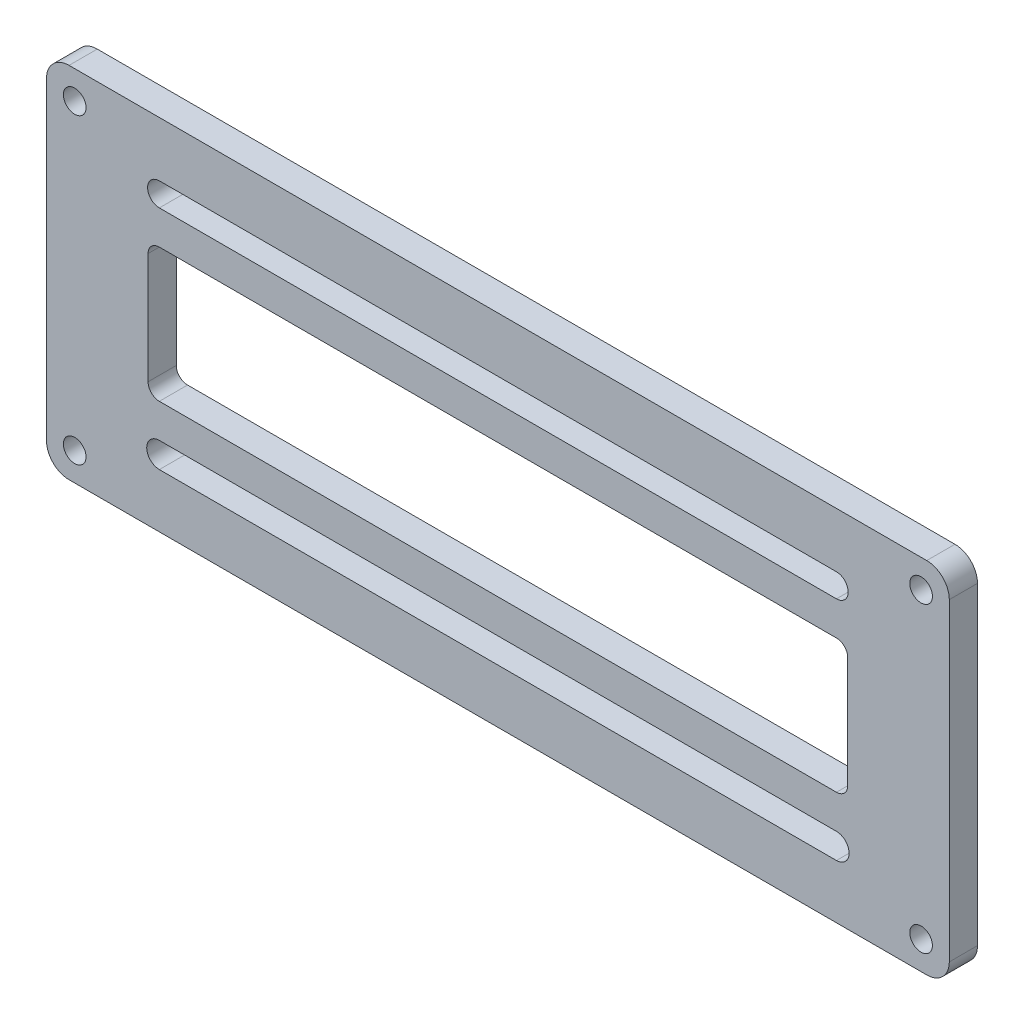
SolidWorks part; units mm, degrees
ref_plane "Front Plane" through (0, 0, 0) normal (0, 0, 1) x (1, 0, 0)
ref_plane "Top Plane" through (0, 0, 0) normal (0, 1, 0) x (1, 0, 0)
ref_plane "Right Plane" through (0, 0, 0) normal (1, 0, 0) x (0, 0, -1)
sketch "Sketch1" plane through (0, 0, 0) normal (0, 0, 1) x (1, 0, 0)
  line L1 (-74.3372, -32.278) -> (128.8628, -32.278)
  line L2 (-74.3372, -32.278) -> (-74.3372, 48.494)
  line L3 (-74.3372, 48.494) -> (128.8628, 48.494)
  line L4 (128.8628, -32.278) -> (128.8628, 48.494)
  dimension "D1" = 80.772
  dimension "D2" = 203.2
extrude "Boss-Extrude1" add sketch "Sketch1" along normal blind 6.35
sketch "Sketch2" plane through (0, 0, 6.35) normal (0, 0, 1) x (1, 0, 0)
  line L0 (128.8628, 48.494) -> (-74.3372, 48.494) construction
  line L1 (128.8628, -32.278) -> (128.8628, 48.494) construction
  line L2 (-74.3372, -32.278) -> (128.8628, -32.278) construction
  line L3 (-74.3372, 48.494) -> (-74.3372, -32.278) construction
  circle A0 centre (-67.9872, 42.144) radius 2.5527
  circle A1 centre (-67.9872, -25.928) radius 2.5527
  circle A2 centre (122.5128, 42.144) radius 2.5527
  circle A3 centre (122.5128, -25.928) radius 2.5527
  dimension "D1" = 5.1054
  dimension "D4" = 5.1054
  dimension "D5" = 6.35
  dimension "D6" = 196.85
  dimension "D7" = 5.1054
  dimension "D8" = 5.1054
  dimension "D9" = 6.35
  dimension "D10" = 6.35
  dimension "D11" = 196.85
  dimension "D12" = 196.85
  dimension "D2" = 6.35
  dimension "D3" = 196.85
extrude "Cut-Extrude1" cut sketch "Sketch2" against normal blind 8.89
sketch "Sketch3" plane through (0, 0, 6.35) normal (0, 0, 1) x (1, 0, 0)
  line L0 (-48.9372, 33.508) -> (103.4628, 33.508) construction
  line L1 (-48.9372, 36.1475) -> (103.4628, 36.1475)
  line L2 (-48.9372, 30.8685) -> (103.4628, 30.8685)
  line L3 (-48.9372, -17.292) -> (103.4628, -17.292) construction
  line L4 (-48.9372, -14.4494) -> (103.4628, -14.4494)
  line L5 (-48.9372, -20.1346) -> (103.4628, -20.1346)
  line L6 (-74.3372, 48.494) -> (-74.3372, -32.278) construction
  line L7 (-74.3372, -32.278) -> (128.8628, -32.278) construction
  line L9 (-48.9372, -6.8294) -> (103.4628, -6.8294)
  line L10 (-51.4772, -4.2894) -> (-51.4772, 20.6945)
  line L11 (-48.9372, 23.2345) -> (103.4628, 23.2345)
  line L12 (106.0028, -4.2894) -> (106.0028, 20.6945)
  arc A0 (-48.9372, 36.1475) -> (-48.9372, 30.8685) centre (-48.9372, 33.508) ccw
  arc A1 (103.4628, 30.8685) -> (103.4628, 36.1475) centre (103.4628, 33.508) ccw
  arc A2 (-48.9372, -14.4494) -> (-48.9372, -20.1346) centre (-48.9372, -17.292) ccw
  arc A3 (103.4628, -20.1346) -> (103.4628, -14.4494) centre (103.4628, -17.292) ccw
  arc A4 (103.4628, -6.8294) -> (106.0028, -4.2894) centre (103.4628, -4.2894) ccw
  arc A5 (103.4628, 23.2345) -> (106.0028, 20.6945) centre (103.4628, 20.6945) cw
  arc A6 (-48.9372, -6.8294) -> (-51.4772, -4.2894) centre (-48.9372, -4.2894) cw
  arc A7 (-51.4772, 20.6945) -> (-48.9372, 23.2345) centre (-48.9372, 20.6945) cw
  point P2 (27.2628, 33.508)
  point P7 (27.2628, -17.292)
  dimension "D7" = 2.54
  dimension "D1" = 25.4
  dimension "D2" = 152.4
  dimension "D3" = 152.4
  dimension "D4" = 25.4
  dimension "D5" = 65.786
  dimension "D6" = 14.986
  dimension "D8" = 152.4
  dimension "D9" = 25.4
  dimension "D10" = 7.634
  dimension "D11" = 7.62
extrude "Cut-Extrude2" cut sketch "Sketch3" against normal blind 13.97
fillet "Fillet1" radius 5.08 4 edges at (-74.3372, -32.278, 3.175) (-74.3372, 48.494, 3.175) (128.8628, -32.278, 3.175) (128.8628, 48.494, 3.175)
